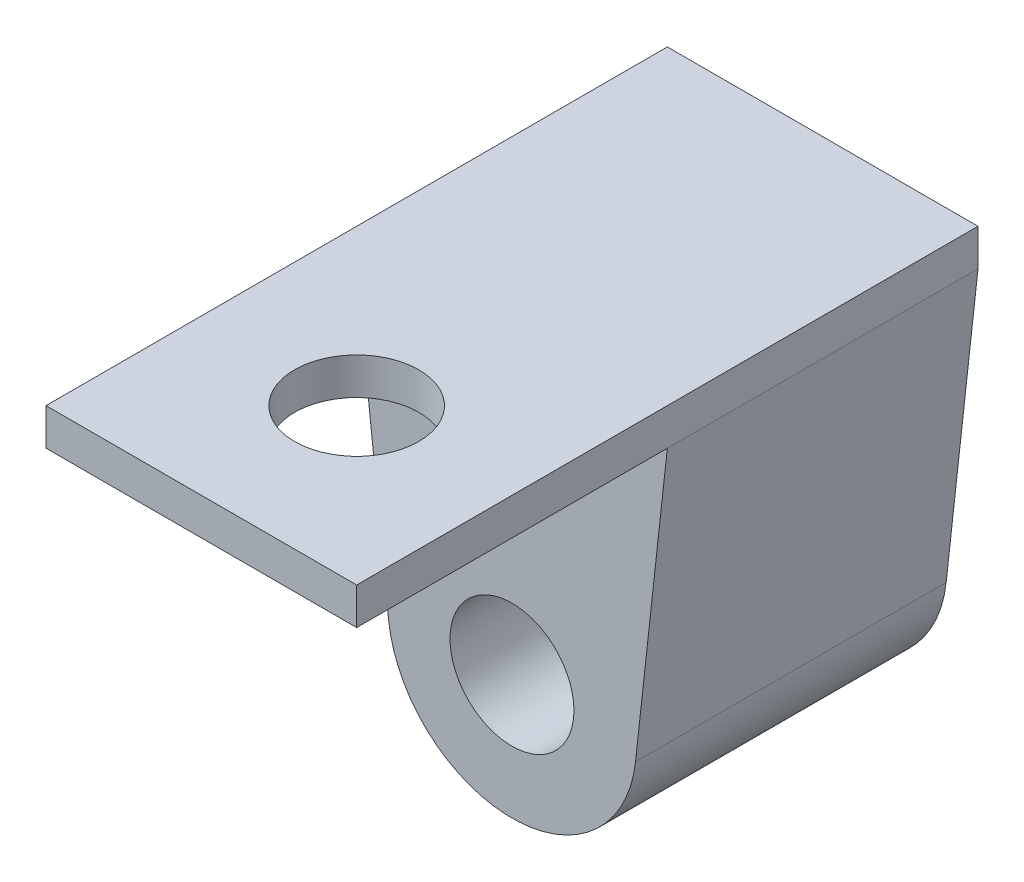
SolidWorks part; units mm, degrees
ref_plane "Front Plane" through (0, 0, 0) normal (0, 0, 1) x (1, 0, 0)
ref_plane "Top Plane" through (0, 0, 0) normal (0, 1, 0) x (1, 0, 0)
ref_plane "Right Plane" through (0, 0, 0) normal (1, 0, 0) x (0, 0, -1)
sketch "Sketch2" plane through (0, 0, 0) normal (0, 0, 1) x (1, 0, 0)
  line L0 (0, -8.5276) -> (0, -0.6089) construction
  line L1 (2.5, -0.1619) -> (2.5, 0.4318)
  line L2 (-2.5, -0.1619) -> (-1.9879, -4.7883)
  line L3 (-2.5, -0.1619) -> (-2.5, 0.4318)
  line L4 (-2.5, 0.4318) -> (2.5, 0.4318)
  line L5 (2.5, -0.1619) -> (1.9879, -4.7883)
  line L6 (2.5, -0.1619) -> (-2.5, -0.1619)
  arc A0 (-1.9879, -4.7883) -> (1.9879, -4.7883) centre (0, -4.5682) ccw
  circle A1 centre (0, -4.5682) radius 0.9975
  point P2 (0, 0.4318)
  point P7 (0, -4.5682)
  dimension "D1" = 1.995
  dimension "D2" = 4
  dimension "D3" = 5
  dimension "D4" = 5
extrude "Boss-Extrude2" add sketch "Sketch2" along normal blind 5
ref_plane "Plane1" through (0, 0, 5) normal (0, 0, 1) x (1, 0, 0)
sketch "Sketch3" plane through (0, 0, 5) normal (0, 0, 1) x (1, 0, 0)
  line L1 (2.5, -0.1619) -> (-2.5, -0.1619)
  line L2 (2.5, -0.1619) -> (2.5, 0.4318)
  line L3 (2.5, 0.4318) -> (-2.5, 0.4318)
  line L4 (-2.5, -0.1619) -> (-2.5, 0.4318)
extrude "Boss-Extrude3" add sketch "Sketch3" along normal blind 5
sketch "Sketch8" plane through (0, -0.1619, 0) normal (0, -1, 0) x (-1, 0, 0)
  line L0 (2.5, -10) -> (-2.5, -10) construction
  circle A0 centre (0, -7.5) radius 1
  point P4 (0, -10)
  dimension "D2" = 2
  dimension "D1" = 2.5
extrude "Cut-Extrude2" cut sketch "Sketch8" against normal blind 5
